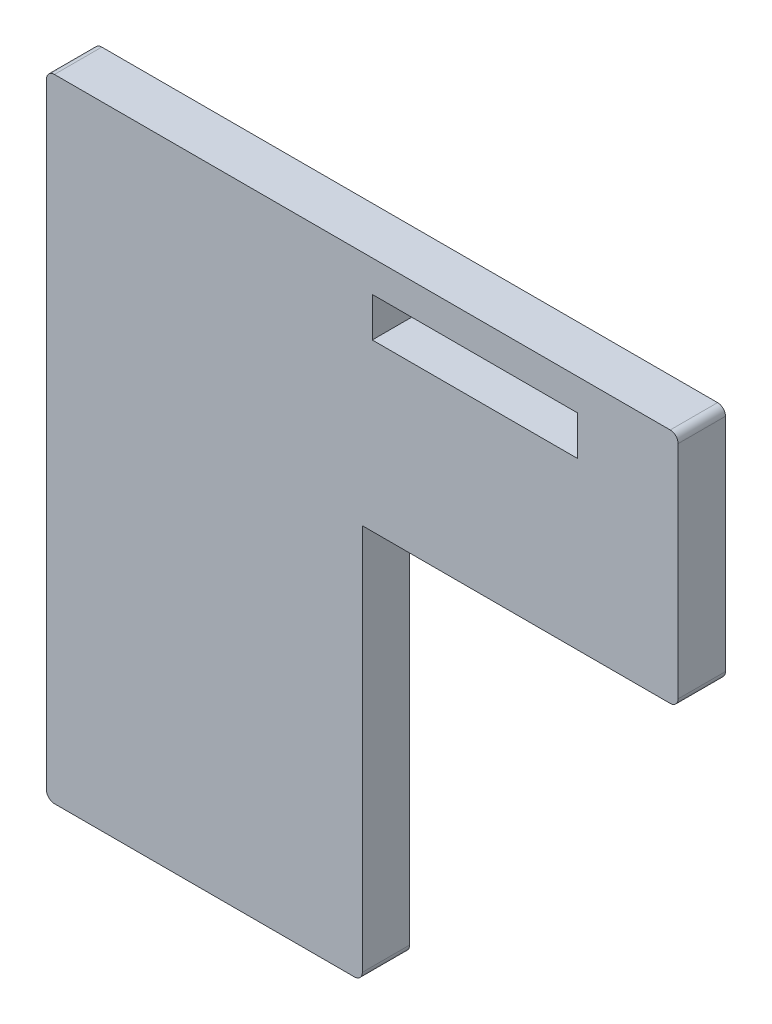
SolidWorks part; units mm, degrees
ref_plane "Ön Düzlem" through (0, 0, 0) normal (0, 0, 1) x (1, 0, 0)
ref_plane "Üst Düzlem" through (0, 0, 0) normal (0, 1, 0) x (1, 0, 0)
ref_plane "Sağ Düzlem" through (0, 0, 0) normal (1, 0, 0) x (0, 0, -1)
sketch "Çizim1" plane through (0, 0, 0) normal (0, 0, 1) x (1, 0, 0)
  line L0 (-39.3368, 0) -> (0, 0) construction
  line L5 (0, 22.9268) -> (0, 11.75) construction
  line L6 (10, 21.25) -> (30, 21.25)
  line L7 (-10, 21.25) -> (10, 21.25)
  line L8 (-10, 21.25) -> (-10, -18.75)
  line L9 (-10, -18.75) -> (10, -18.75)
  line L10 (10, 6.25) -> (10, -18.75)
  line L11 (30, 21.25) -> (30, 6.25)
  line L12 (30, 6.25) -> (10, 6.25)
  line L14 (6.5, 0) -> (31.0415, 0) construction
  dimension "D3" = 40
  dimension "D4" = 20
  dimension "D5" = 20
  dimension "D6" = 15
extrude "Yükseklik-Ekstrüzyon1" add sketch "Çizim1" along normal blind 3
fillet "Radyus1" radius 0.5 5 edges at (-10, 21.25, 1.5) (-10, -18.75, 1.5) (10, -18.75, 1.5) (30, 6.25, 1.5) (30, 21.25, 1.5)
sketch "Çizim6" plane through (0, 0, 0) normal (0, 0, -1) x (-1, 0, 0)
  line L0 (-29.5, 21.25) -> (9.5, 21.25) construction
  line L1 (-23.6302, 19.25) -> (-10.6302, 19.25)
  line L2 (-23.6302, 19.25) -> (-23.6302, 16.75)
  line L3 (-23.6302, 16.75) -> (-10.6302, 16.75)
  line L4 (-10.6302, 19.25) -> (-10.6302, 16.75)
  dimension "D1" = 13
  dimension "D2" = 2.5
  dimension "D3" = 2
extrude "Kes-Ekstrüzyon2" cut sketch "Çizim6" against normal up to next
